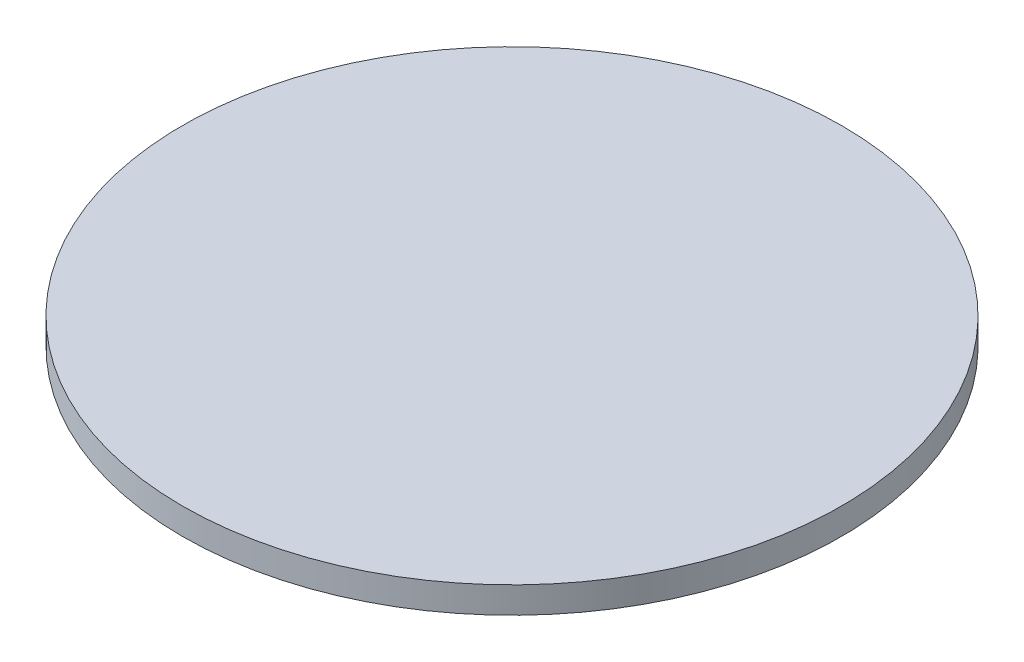
SolidWorks part; units mm, degrees
ref_plane "Front Plane" through (0, 0, 0) normal (0, 0, 1) x (1, 0, 0)
ref_plane "Top Plane" through (0, 0, 0) normal (0, 1, 0) x (1, 0, 0)
ref_plane "Right Plane" through (0, 0, 0) normal (1, 0, 0) x (0, 0, -1)
sketch "Sketch1" plane through (0, 0, 0) normal (0, 1, 0) x (1, 0, 0)
  circle A0 centre (0, 0) radius 37.5
  point P3 (0, 0)
  dimension "D1" = 37.5
extrude "Boss-Extrude1" add sketch "Sketch1" along normal blind 3
equation "\"Rocket_Radius_Internal\"=37.5"
equation "\"D1@Sketch1\"=\"Rocket_Radius_Internal\""
equation "\"ABS_Thickness\"= 3"
equation "\"D1@Boss-Extrude1\"=\"ABS_Thickness\""
